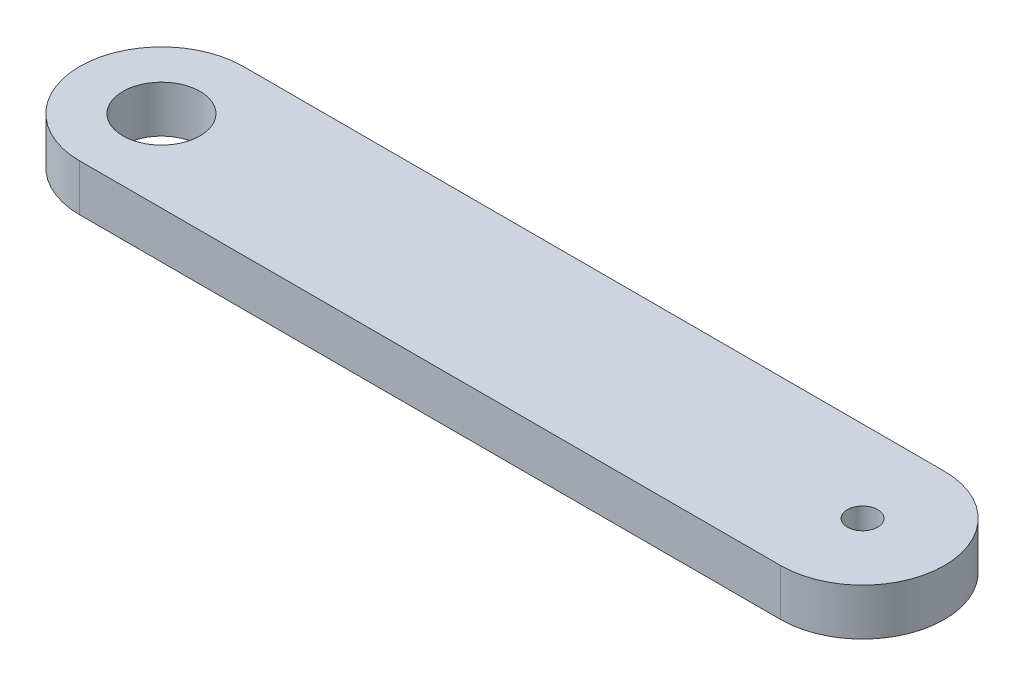
SolidWorks part; units mm, degrees
ref_plane "Front Plane" through (0, 0, 0) normal (0, 0, 1) x (1, 0, 0)
ref_plane "Top Plane" through (0, 0, 0) normal (0, 1, 0) x (1, 0, 0)
ref_plane "Right Plane" through (0, 0, 0) normal (1, 0, 0) x (0, 0, -1)
sketch "Sketch1" plane through (0, 0, 0) normal (0, 1, 0) x (1, 0, 0)
  line L0 (0, 0) -> (150, 0) construction
  line L1 (0, 17.5) -> (150, 17.5)
  line L2 (0, -17.5) -> (150, -17.5)
  arc A0 (0, 17.5) -> (0, -17.5) centre (0, 0) ccw
  arc A1 (150, -17.5) -> (150, 17.5) centre (150, 0) ccw
  circle A2 centre (0, 0) radius 8.25
  circle A3 centre (150, 0) radius 3.25
  point P3 (75, 0)
  dimension "D1" = 16.5
  dimension "D2" = 6.5
  dimension "D3" = 35
  dimension "D4" = 150
extrude "Boss-Extrude1" add sketch "Sketch1" along normal blind 10
